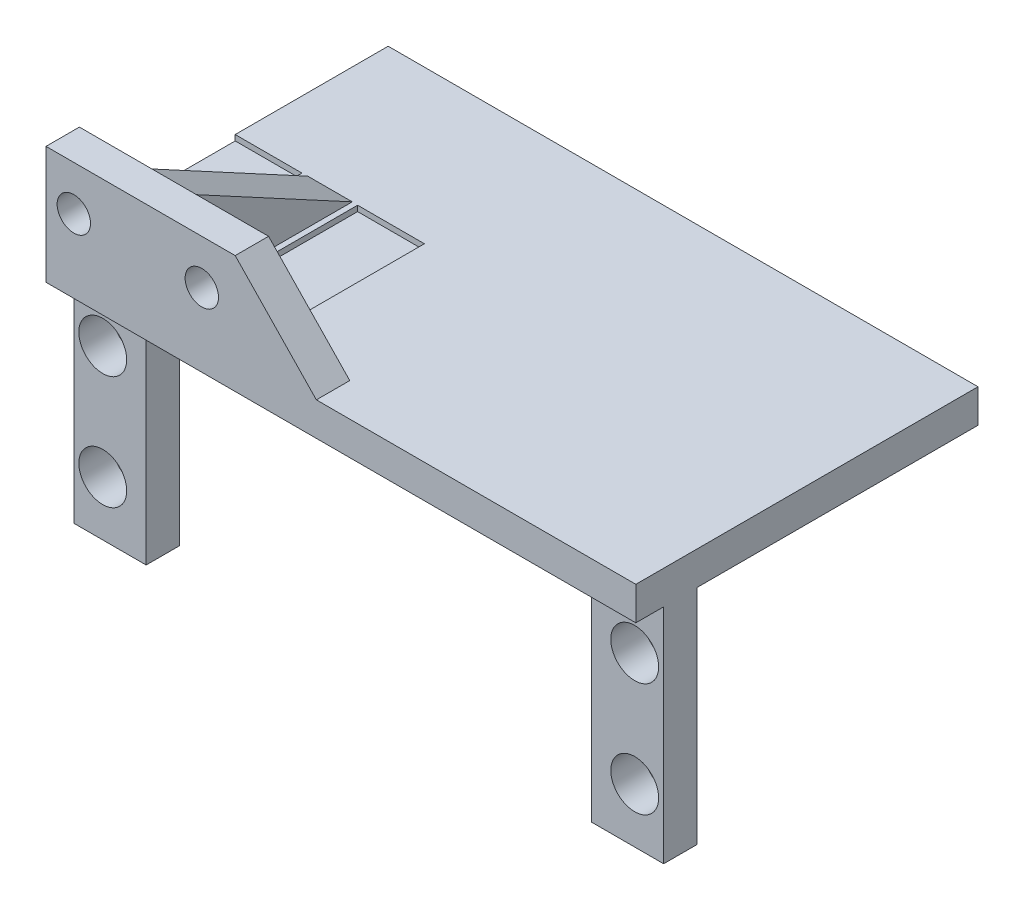
SolidWorks part; units mm, degrees
ref_plane "Front Plane" through (0, 0, 0) normal (0, 0, 1) x (1, 0, 0)
ref_plane "Top Plane" through (0, 0, 0) normal (0, 1, 0) x (1, 0, 0)
ref_plane "Right Plane" through (0, 0, 0) normal (1, 0, 0) x (0, 0, -1)
sketch "Sketch1" plane through (0, 0, 0) normal (0, 1, 0) x (1, 0, 0)
  line L1 (-2.3819, -6.7453) -> (50.6181, -6.7453)
  line L2 (-2.3819, -6.7453) -> (-2.3819, -37.4909)
  line L3 (-2.3819, -37.4909) -> (50.6181, -37.4909)
  line L4 (50.6181, -6.7453) -> (50.6181, -37.4909)
  dimension "D1" = 30.7456
  dimension "D2" = 53
extrude "Boss-Extrude1" add sketch "Sketch1" along normal blind 3
sketch "Sketch2" plane through (0, 0, 0) normal (0, -1, 0) x (1, 0, 0)
  line L1 (50.6181, 34.9909) -> (44.1181, 34.9909)
  line L2 (50.6181, 34.9909) -> (50.6181, 31.9909)
  line L3 (50.6181, 31.9909) -> (44.1181, 31.9909)
  line L4 (44.1181, 34.9909) -> (44.1181, 31.9909)
  line L6 (44.1181, 23.4909) -> (44.1181, 52.9909) construction
  line L7 (-2.3819, 6.7453) -> (-2.3819, 37.4909) construction
  line L8 (4.1181, 34.9909) -> (-2.3819, 34.9909)
  line L9 (4.1181, 34.9909) -> (4.1181, 31.9909)
  line L10 (4.1181, 31.9909) -> (-2.3819, 31.9909)
  line L11 (-2.3819, 34.9909) -> (-2.3819, 31.9909)
  line L14 (-2.3819, 37.4909) -> (50.6181, 37.4909) construction
  line L15 (50.6181, 6.7453) -> (-2.3819, 6.7453) construction
  dimension "D1" = 3
  dimension "D2" = 3
  dimension "D3" = 2.5
  dimension "D4" = 25.2456
  dimension "D5" = 6.5
  dimension "D6" = 2.5
  dimension "D7" = 3
  dimension "D8" = 6.5
  dimension "D9" = 6.5
extrude "Boss-Extrude2" add sketch "Sketch2" along normal blind 20
sketch "Sketch3" plane through (0, 0, 34.9909) normal (0, 0, 1) x (1, 0, 0)
  line L0 (-2.3819, -20) -> (-2.3819, 0) construction
  line L2 (-2.3819, 3) -> (50.6181, 3) construction
  line L3 (50.6181, -20) -> (50.6181, 0) construction
  circle A0 centre (48.0181, -15.1) radius 2.15
  circle A1 centre (48.0181, -4.9) radius 2.15
  circle A2 centre (0.2181, -15.1) radius 2.15
  circle A3 centre (0.2181, -4.9) radius 2.15
  dimension "D1" = 4.3
  dimension "D2" = 4.3
  dimension "D3" = 4.3
  dimension "D4" = 4.3
  dimension "D5" = 2.6
  dimension "D6" = 7.9
  dimension "D7" = 10.2
  dimension "D8" = 2.6
  dimension "D9" = 7.9
  dimension "D10" = 10.2
extrude "Cut-Extrude1" cut sketch "Sketch3" against normal blind 3
sketch "Sketch6" plane through (0, 0, 37.4909) normal (0, 0, 1) x (1, 0, 0)
  line L1 (-2.3819, 3) -> (14.6181, 3)
  line L2 (-2.3819, 3) -> (-2.3819, 10.58)
  line L3 (-2.3819, 10.58) -> (14.6181, 10.58)
  line L4 (14.6181, 3) -> (14.6181, 10.58)
  dimension "D1" = 17
  dimension "D2" = 7.58
extrude "Boss-Extrude3" add sketch "Sketch6" against normal blind 3
sketch "Sketch7" plane through (0, 0, 37.4909) normal (0, 0, 1) x (1, 0, 0)
  line L0 (14.6181, 3) -> (14.6181, 10.58) construction
  line L1 (14.6181, 10.58) -> (-2.3819, 10.58) construction
  circle A1 centre (0.1181, 6.58) radius 1.5
  circle A3 centre (11.6181, 6.58) radius 1.5
  dimension "D1" = 3
  dimension "D2" = 3
  dimension "D3" = 3
  dimension "D4" = 4
  dimension "D5" = 11.5
extrude "Cut-Extrude2" cut sketch "Sketch7" against normal blind 7.5
sketch "Sketch8" plane through (0, 3, 0) normal (0, 1, 0) x (1, 0, 0)
  line L1 (-2.3819, -34.4909) -> (3.6181, -34.4909)
  line L2 (-2.3819, -34.4909) -> (-2.3819, -20.4909)
  line L3 (-2.3819, -20.4909) -> (3.6181, -20.4909)
  line L4 (3.6181, -34.4909) -> (3.6181, -20.4909)
  line L6 (-2.3819, -6.7453) -> (-2.3819, -34.4909)
  line L7 (-2.3819, -34.4909) -> (14.6181, -34.4909)
  line L8 (14.6181, -34.4909) -> (14.6181, -37.4909)
  line L9 (14.6181, -37.4909) -> (50.6181, -37.4909)
  line L10 (50.6181, -37.4909) -> (50.6181, -6.7453)
  line L11 (50.6181, -6.7453) -> (-2.3819, -6.7453)
  line L16 (50.6181, -37.4909) -> (50.6181, -6.7453)
  line L18 (14.6181, -34.4909) -> (8.6181, -34.4909)
  line L19 (14.6181, -34.4909) -> (14.6181, -20.4909)
  line L20 (14.6181, -20.4909) -> (8.6181, -20.4909)
  line L21 (8.6181, -34.4909) -> (8.6181, -20.4909)
  line L22 (14.6181, -37.4909) -> (50.6181, -37.4909) construction
  line M15 (-2.3819, -6.7453) -> (-2.3819, -34.4909)
  line M16 (-2.3819, -34.4909) -> (14.6181, -34.4909)
  dimension "D2" = 6
  dimension "D3" = 6
  dimension "D4" = 17
  dimension "D1" = 0
extrude "Cut-Extrude3" cut sketch "Sketch8" against normal blind 0.5 contours L21 L19 L20 M16 | L4 L3 M16 M15
fillet "Fillet1" [suppressed] radius 2
ref_plane "Plane1" through (6.1181, 0, 0) normal (-1, 0, 0) x (0, 0, 1)
sketch "Sketch13" plane through (6.1181, 0, 0) normal (-1, 0, 0) x (0, 0, 1)
  line L0 (34.4909, 10.5703) -> (34.4909, 3)
  line L1 (34.4909, 10.58) -> (34.4909, 2.5) construction
  line L2 (34.4909, 3) -> (20.4689, 3)
  line L4 (20.4689, 3) -> (34.4909, 10.5703)
extrude "Boss-Extrude4" add sketch "Sketch13" along normal blind 2 and the other way blind 2
sketch "Sketch14" plane through (0, 0, 37.4909) normal (0, 0, 1) x (1, 0, 0)
  line L0 (14.6181, 3) -> (14.6181, 10.58)
  line L1 (14.6181, 3) -> (21.9121, 3)
  line L2 (14.6181, 3) -> (50.6181, 3) construction
  line L3 (21.9121, 3) -> (14.6181, 10.58)
extrude "Boss-Extrude5" add sketch "Sketch14" against normal blind 3
